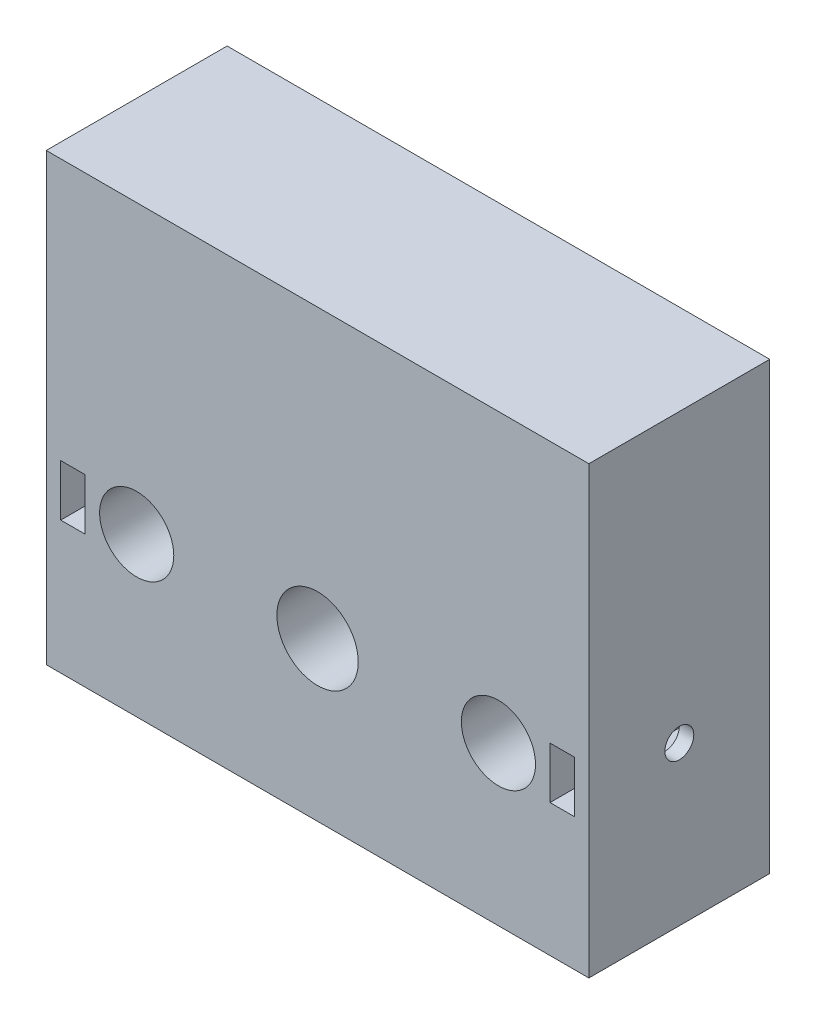
SolidWorks part; units mm, degrees
ref_plane "前视基准面" through (0, 0, 0) normal (0, 0, 1) x (1, 0, 0)
ref_plane "上视基准面" through (0, 0, 0) normal (0, 1, 0) x (1, 0, 0)
ref_plane "右视基准面" through (0, 0, 0) normal (1, 0, 0) x (0, 0, -1)
other "Configuration Table"
sketch "草图1" plane through (0, 0, 0) normal (0, 0, 1) x (1, 0, 0)
  line L1 (-30, -17.5) -> (30, -17.5)
  line L2 (-30, -17.5) -> (-30, 17.5)
  line L3 (-30, 17.5) -> (30, 17.5)
  line L4 (30, -17.5) -> (30, 17.5)
  line L5 (-30, -17.5) -> (30, 17.5) construction
  line L6 (-30, 17.5) -> (30, -17.5) construction
  point P0 (0, 0)
  dimension "D1" = 60
  dimension "D2" = 35
extrude "凸台-拉伸1" add sketch "草图1" along normal blind 20
hole_wizard "光轴孔" positions "草图2" profile "草图3" legacy end condition through all
sketch "草图2" plane through (0, 0, 20) normal (0, 0, 1) x (1, 0, 0)
  point P0 (0, 0)
sketch "草图3" plane through (0, 0, 20) normal (1, 0, 0) x (0, -1, 0)
  line L0 (0, 0) -> (0, 20)
  line L1 (0, 20) -> (4.5, 20)
  line L2 (4.5, 20) -> (4.5, 0)
  line L3 (4.5, 0) -> (0, 0)
  line L4 (0, 110) -> (0, -10) construction
  dimension "直径" = 9
  dimension "深度" = 20
hole_wizard "直线轴承座孔" positions "草图6" profile "草图7" legacy end condition through all
sketch "草图6" plane through (0, 0, 20) normal (0, 0, 1) x (1, 0, 0)
  point P0 (20, 0)
  point P2 (-20, 0)
  dimension "D1" = 20
  dimension "D2" = 20
sketch "草图7" plane through (20, 0, 20) normal (1, 0, 0) x (0, -1, 0)
  line L0 (0, 0) -> (0, 20)
  line L1 (0, 20) -> (4.1, 20)
  line L2 (4.1, 20) -> (4.1, 0)
  line L3 (4.1, 0) -> (0, 0)
  line L4 (0, 110) -> (0, -10) construction
  dimension "直径" = 8.2
  dimension "深度" = 20
sketch "草图8" plane through (0, 0, 20) normal (0, 0, 1) x (1, 0, 0)
  line L0 (30, 0) -> (24.1, 0) construction
  line L1 (30, -17.5) -> (30, 17.5) construction
  line L3 (25.7, -2.85) -> (28.4, -2.85)
  line L4 (25.7, -2.85) -> (25.7, 2.85)
  line L5 (25.7, 2.85) -> (28.4, 2.85)
  line L6 (28.4, -2.85) -> (28.4, 2.85)
  line L7 (25.7, -2.85) -> (28.4, 2.85) construction
  line L8 (25.7, 2.85) -> (28.4, -2.85) construction
  circle A0 centre (20, 0) radius 4.1 construction
  point P7 (27.05, 0)
  dimension "D1" = 2.7
  dimension "D2" = 5.7
extrude "切除-拉伸1" cut sketch "草图8" against normal through all
ref_plane "基准面1" through (0, 0, 0) normal (1, 0, 0) x (0, 0, -1)
sketch "草图9" plane through (30, 0, 0) normal (1, 0, 0) x (0, 0, -1)
  line L0 (-20, 0) -> (0, 0) construction
  line L1 (-20, -17.5) -> (-20, 17.5) construction
  circle A0 centre (-10, 0) radius 1.6
  dimension "D1" = 3.2
extrude "切除-拉伸2" cut sketch "草图9" against normal blind 10
mirror "镜向1" about plane through (0, 0, 0) normal (1, 0, 0) of "切除-拉伸2", "切除-拉伸1"
sketch "草图10" plane through (0, 17.5, 0) normal (0, 1, 0) x (1, 0, 0)
  line L1 (-30, 0) -> (30, 0)
  line L2 (-30, 0) -> (-30, -20)
  line L3 (-30, -20) -> (30, -20)
  line L4 (30, 0) -> (30, -20)
extrude "凸台-拉伸2" add sketch "草图10" along normal blind 14.25
